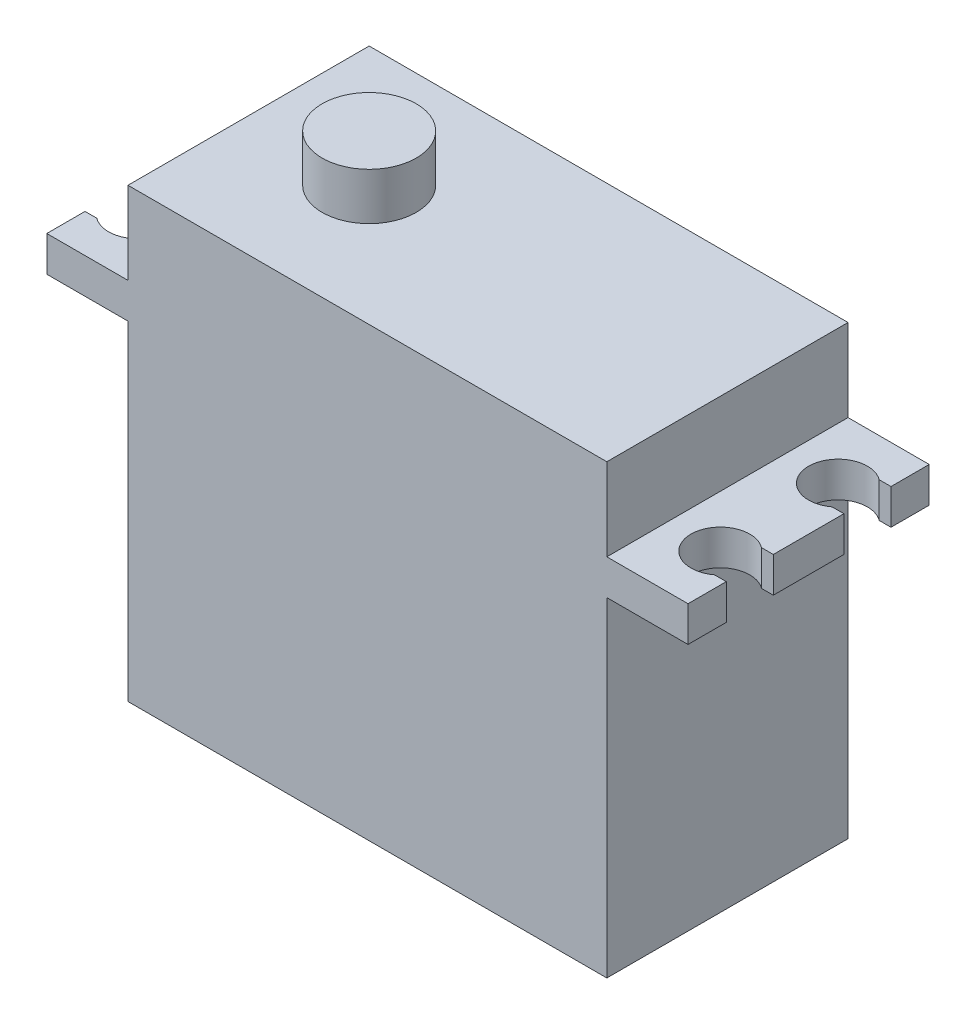
SolidWorks part; units mm, degrees
ref_plane "Front Plane" through (0, 0, 0) normal (0, 0, 1) x (1, 0, 0)
ref_plane "Top Plane" through (0, 0, 0) normal (0, 1, 0) x (1, 0, 0)
ref_plane "Right Plane" through (0, 0, 0) normal (1, 0, 0) x (0, 0, -1)
sketch "Sketch1" plane through (0, 0, 0) normal (0, 1, 0) x (1, 0, 0)
  line L1 (0, 0) -> (40.7, 0)
  line L2 (0, 0) -> (0, 20.5)
  line L3 (0, 20.5) -> (40.7, 20.5)
  line L4 (40.7, 0) -> (40.7, 20.5)
  dimension "D1" = 40.7
  dimension "D2" = 20.5
extrude "Boss-Extrude1" add sketch "Sketch1" along normal blind 38
sketch "Sketch2" plane through (0, 38, 0) normal (0, 1, 0) x (1, 0, 0)
  line L0 (0, 20.5) -> (0, 0) construction
  line L1 (40.7, 20.5) -> (0, 20.5) construction
  circle A0 centre (10.25, 10.25) radius 4
  point P6 (-14.4862, 36.665)
  dimension "D3" = 8
  dimension "D1" = 10.25
  dimension "D2" = 10.25
extrude "Boss-Extrude2" add sketch "Sketch2" along normal offset from surface (4 mm away) 42 up to face at (20.35, 0, -10.25)
ref_plane "Plane1" through (0, 28, 0) normal (0, 1, 0) x (1, 0, 0)
sketch "Sketch3" plane through (0, 28, 0) normal (0, 1, 0) x (1, 0, 0)
  line L0 (40.7, 20.5) -> (0, 20.5) construction
  line L1 (-6.9, 20.5) -> (47.6, 20.5)
  line L2 (-6.9, 20.5) -> (-6.9, 0)
  line L3 (-6.9, 0) -> (47.6, 0)
  line L4 (47.6, 20.5) -> (47.6, 0)
  line L5 (0, 0) -> (40.7, 0) construction
  point P8 (20.35, 0)
  point P9 (20.35, 0)
  dimension "D1" = 54.5
extrude "Boss-Extrude3" add sketch "Sketch3" along normal blind 3
sketch "Sketch4" plane through (0, 28, 0) normal (0, 1, 0) x (1, 0, 0)
  line L1 (40.7, 20.5) -> (0, 20.5) construction
  line L2 (-5.9, 17.25) -> (-6.9, 17.25)
  line L3 (-6.9, 20.5) -> (-6.9, 0) construction
  line L4 (-6.9, 17.25) -> (-6.9, 13.25)
  line L5 (-6.9, 13.25) -> (-5.9, 13.25)
  circle A0 centre (10.25, 10.25) radius 4 construction
  arc A2 (-5.9, 13.25) -> (-5.9, 17.25) centre (-4.4, 15.25) ccw
  point P8 (-6.1444, 12.75)
  point P15 (20.35, 20.5)
  point P20 (-6.1444, 13.7426)
  dimension "D4" = 5
  dimension "D6" = 24.75
  dimension "D1" = 5
  dimension "D7" = 4
  dimension "D8" = 2
extrude "Cut-Extrude1" cut sketch "Sketch4" along normal through all
ref_plane "Plane2" through (0, 0, -10.25) normal (0, 0, -1) x (-1, 0, 0)
ref_plane "Plane3" through (20.35, 0, 0) normal (1, 0, 0) x (0, 0, -1)
mirror "Mirror1" about plane through (0, 0, -10.25) normal (0, 0, -1) of "Cut-Extrude1"
mirror "Mirror2" about plane through (20.35, 0, 0) normal (1, 0, 0) of "Mirror1", "Cut-Extrude1"
